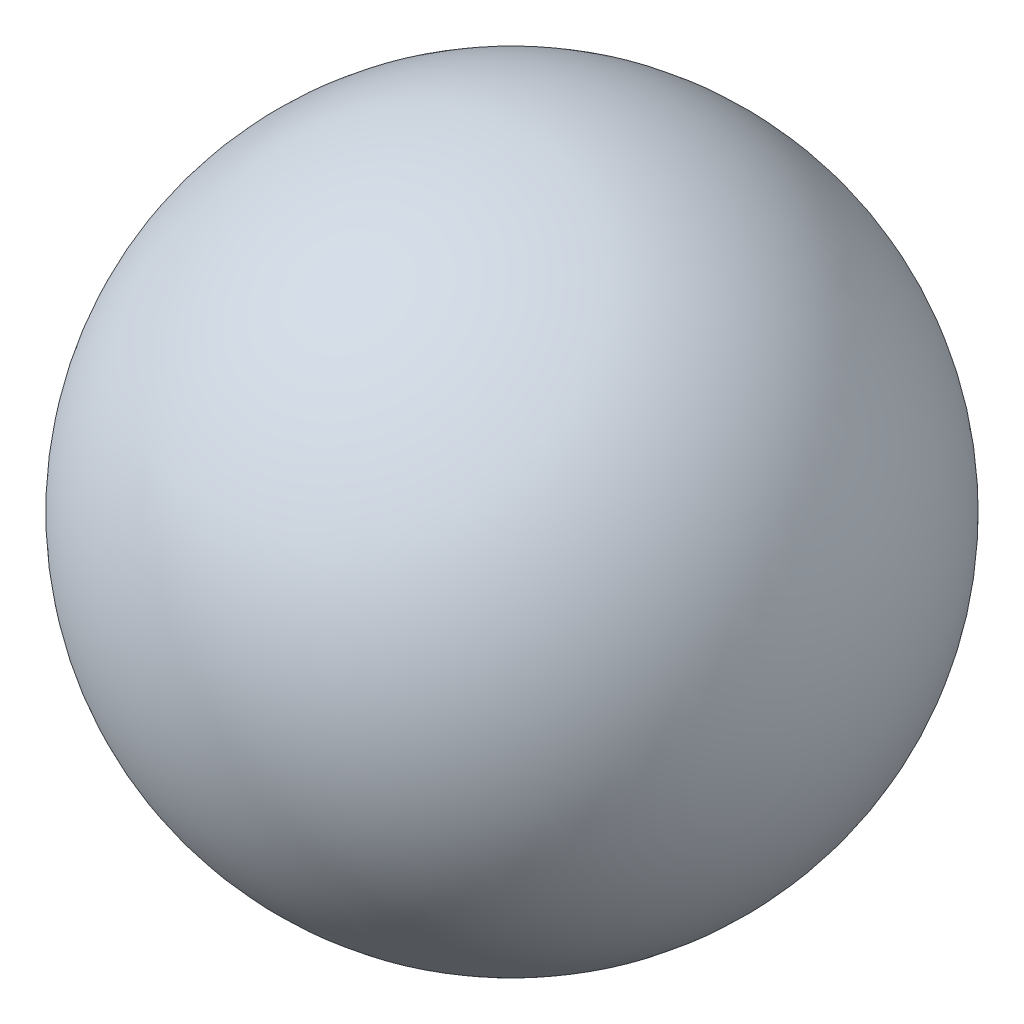
SolidWorks part; units mm, degrees
ref_plane "Спереди" through (0, 0, 0) normal (0, 0, 1) x (1, 0, 0)
ref_plane "Сверху" through (0, 0, 0) normal (0, 1, 0) x (1, 0, 0)
ref_plane "Справа" through (0, 0, 0) normal (1, 0, 0) x (0, 0, -1)
sketch "Эскиз1" plane through (0, 0, 0) normal (1, 0, 0) x (0, 0, -1)
  line L0 (0, 17.962) -> (0, -24.2097) construction
  line L1 (0, 3.5) -> (0, -3.5)
  arc A0 (0, -3.5) -> (0, 3.5) centre (0, 0) ccw
  dimension "D1" = 7
revolve "Повернуть1" add sketch "Эскиз1" angle 360 about L0
